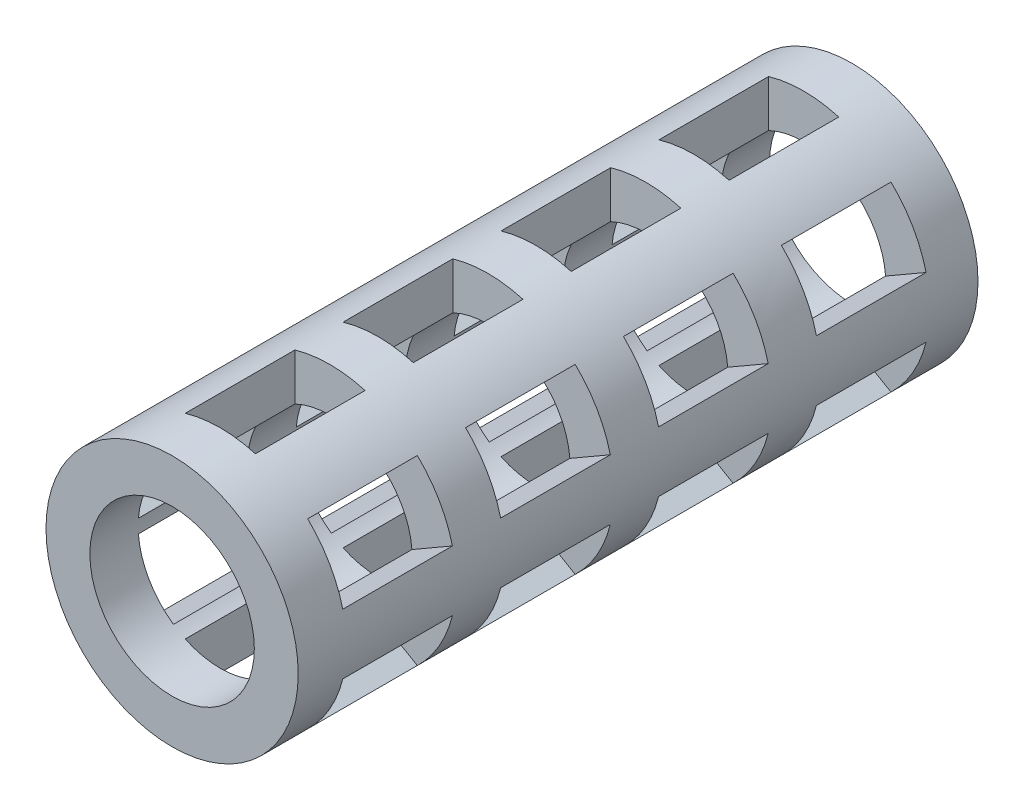
SolidWorks part; units mm, degrees
ref_plane "前视基准面" through (0, 0, 0) normal (0, 0, 1) x (1, 0, 0)
ref_plane "上视基准面" through (0, 0, 0) normal (0, 1, 0) x (1, 0, 0)
ref_plane "右视基准面" through (0, 0, 0) normal (1, 0, 0) x (0, 0, -1)
other "Configuration Table"
sketch "草图1" plane through (0, 0, 0) normal (0, 0, 1) x (1, 0, 0)
  circle A0 centre (0, 0) radius 3.75
  circle A1 centre (0, 0) radius 5.75
  circle A2 centre (0, 0) radius 4.75 construction
  dimension "D1" = 9.5
  dimension "D2" = 1
  dimension "D3" = 1
extrude "凸台-拉伸1" add sketch "草图1" along normal blind 31 contours A2 A0 | A1 A2
sketch "草图2" plane through (0, 0, 0) normal (0, 1, 0) x (1, 0, 0)
  line L0 (0, 0) -> (0, -2.2) construction
  line L1 (-1.6, -2.2) -> (1.6, -2.2)
  line L2 (-1.6, -2.2) -> (-1.6, -7.2)
  line L3 (-1.6, -7.2) -> (1.6, -7.2)
  line L4 (1.6, -2.2) -> (1.6, -7.2)
  line L5 (5.75, 0) -> (-5.75, 0) construction
  line L6 (0, -7.2) -> (0, -9.4) construction
  line L7 (-1.6, -9.4) -> (1.6, -9.4)
  line L8 (-1.6, -9.4) -> (-1.6, -14.4)
  line L9 (-1.6, -14.4) -> (1.6, -14.4)
  line L10 (1.6, -9.4) -> (1.6, -14.4)
  line L11 (-1.6, -16.6) -> (1.6, -16.6)
  line L12 (-1.6, -16.6) -> (-1.6, -21.6)
  line L13 (-1.6, -21.6) -> (1.6, -21.6)
  line L14 (1.6, -16.6) -> (1.6, -21.6)
  line L15 (-1.6, -23.8) -> (1.6, -23.8)
  line L16 (-1.6, -23.8) -> (-1.6, -28.8)
  line L17 (-1.6, -28.8) -> (1.6, -28.8)
  line L18 (1.6, -23.8) -> (1.6, -28.8)
  line L19 (0, -14.4) -> (0, -16.6) construction
  line L20 (0, -21.6) -> (0, -23.8) construction
  line L21 (0, -28.8) -> (0, -31) construction
  line L22 (-5.75, -31) -> (5.75, -31) construction
  dimension "D1" = 3.2
  dimension "D2" = 5
extrude "切除-拉伸1" cut sketch "草图2" against normal through all both and the other way through all
pattern_circular "阵列(圆周)1" count 3 over 360 about axis through (0, 0, 0) along (0, 0, 1) of "切除-拉伸1"
sketch "草图3" plane through (0, 0, 0) normal (0, 0, -1) x (-1, 0, 0)
  line L0 (-3.2476, -1.875) -> (-4.9796, -2.875)
  circle A0 centre (-4.1136, -2.375) radius 0.4856
  circle A1 centre (0, 0) radius 3.75 construction
  circle A2 centre (0, 0) radius 5.75 construction
  arc A3 (3.983, 4.1471) -> (5.583, 1.3758) centre (0, 0) ccw construction
